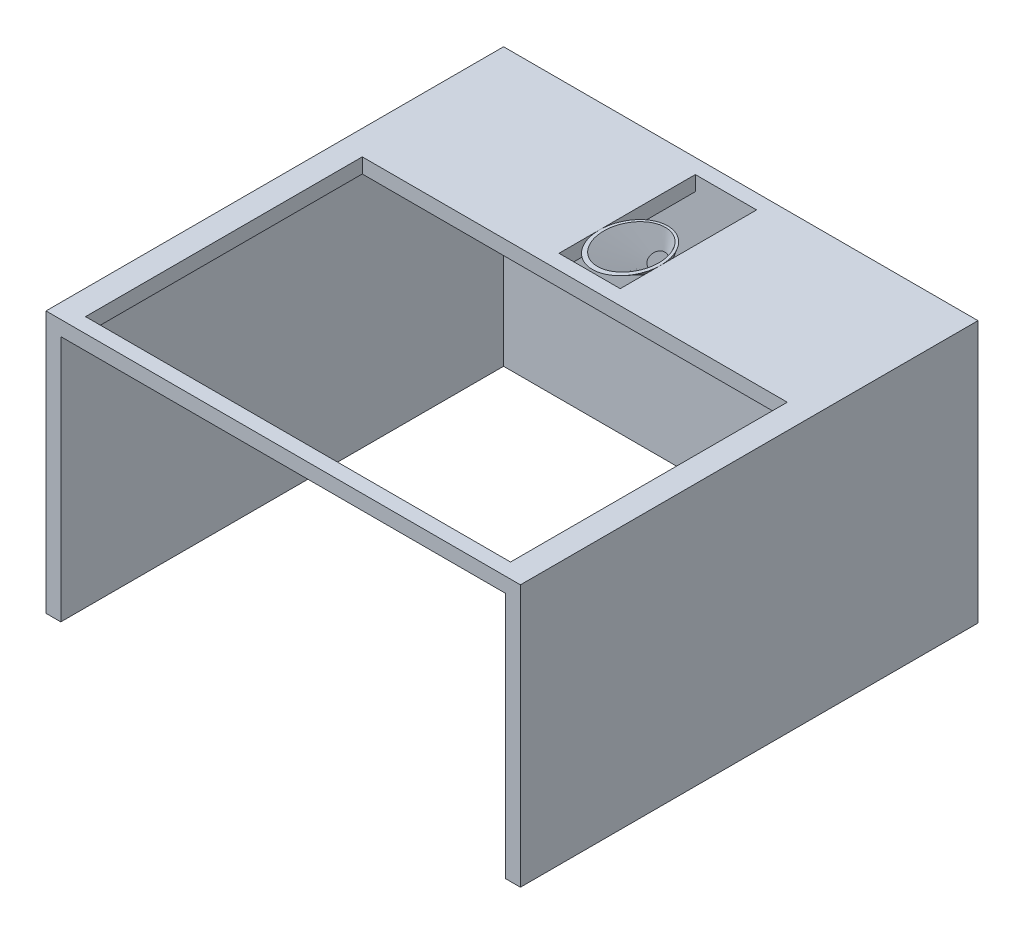
SolidWorks part; units mm, degrees
ref_plane "Front" through (0, 0, 0) normal (0, 0, 1) x (1, 0, 0)
ref_plane "Top" through (0, 0, 0) normal (0, 1, 0) x (1, 0, 0)
ref_plane "Right" through (0, 0, 0) normal (1, 0, 0) x (0, 0, -1)
sketch "Sketch1" plane through (0, 0, 0) normal (0, 1, 0) x (1, 0, 0)
  line L1 (-43, -28) -> (43, -28)
  line L2 (-43, -28) -> (-43, 28)
  line L3 (-43, 28) -> (43, 28)
  line L4 (43, -28) -> (43, 28)
  line L5 (-43, -28) -> (43, 28) construction
  line L6 (-43, 28) -> (43, -28) construction
  line L7 (-48, -31) -> (48, -31)
  line L8 (-48, -31) -> (-48, 31)
  line L9 (-48, 31) -> (48, 31)
  line L10 (48, -31) -> (48, 31)
  line L11 (-48, -31) -> (48, 31) construction
  line L12 (-48, 31) -> (48, -31) construction
  point P0 (0, 0)
  point P6 (0, 0)
  dimension "D1" = 86
  dimension "D2" = 56
  dimension "D3" = 3
  dimension "D4" = 5
extrude "Boss-Extrude1" add sketch "Sketch1" along normal blind 3
sketch "Sketch4" plane through (0, 0, 0) normal (1, 0, 0) x (0, 0, -1)
  line L0 (45.6947, -3.6988) -> (-61.4431, 55.6887) construction
  line L1 (45.6947, -3.6988) -> (-61.4431, 55.6887) construction
  line L2 (32.8171, -9.0552) -> (52.2183, 2.1461) construction
  line L3 (32.8171, -9.0552) -> (52.2183, 2.1461) construction
  line L4 (45.6947, -3.6988) -> (47.8326, 118.7791) construction
  line L5 (45.6947, -3.6988) -> (47.8326, 118.7791) construction
sketch "Sketch5" plane through (0, 0, 0) normal (1, 0, 0) x (0, 0, -1)
  line L0 (45.6947, -3.6988) -> (38.2413, 9.211) construction
  line L1 (32.8171, -9.0552) -> (52.2183, 2.1461) construction
  line L2 (45.6947, -3.6988) -> (-61.4431, 55.6887) construction
  line L3 (43.8581, -2.6807) -> (35.4738, 1.9668)
  line L4 (43.8581, -2.6807) -> (35.4738, 1.9668)
  line L7 (42.8478, -3.264) -> (29.3973, 4.1917)
  line L8 (29.3973, 4.1917) -> (35.4738, 1.9668)
  line L9 (42.8478, -3.264) -> (43.8581, -2.6807)
  line L10 (43.6157, -3.118) -> (32.4355, 3.0793)
  line L11 (43.6157, -3.118) -> (35.2314, 1.5295) construction
  dimension "D1" = 0.5
  dimension "D2" = 0.5
revolve "Revolve4" add sketch "Sketch5" angle 360 about L0
sketch "Sketch6" plane through (0, 0, -31) normal (0, 0, -1) x (-1, 0, 0)
  line L1 (48, 3) -> (-48, 3)
  line L2 (48, 3) -> (48, 16.2937)
  line L3 (48, 16.2937) -> (-48, 16.2937)
  line L4 (-48, 0) -> (48, 0)
  line L5 (48, 0) -> (48, 3)
  line L6 (48, 3) -> (-48, 3)
  line L7 (-48, 3) -> (-48, 0)
  line L8 (-48, 0) -> (48, 0)
  line L9 (48, 0) -> (48, 3)
  line L10 (48, 3) -> (-48, 3)
  line L11 (-48, 3) -> (-48, 0)
  line L12 (-48, 3) -> (-48, 16.2937)
  line M7 (48, 3) -> (-48, 3)
  dimension "D1" = 0
extrude "Cut-Extrude1" cut sketch "Sketch6" along normal through all and the other way through all contours L12 L2 L3 M7
sketch "Sketch7" plane through (0, 0, 0) normal (1, 0, 0) x (0, 0, -1)
  line L13 (32.8171, -19.124) -> (32.8171, -24.1806)
  line L14 (32.8171, -24.1806) -> (37.3171, -21.5825)
  line L15 (37.3171, -21.5825) -> (37.3171, -14.2513)
  line L16 (37.3171, -14.2513) -> (39.4389, -13.0263)
  line L17 (39.4389, -13.0263) -> (38.4389, -11.2943)
  line L18 (38.4389, -11.2943) -> (55.846, -1.2443)
  line L19 (55.846, -1.2443) -> (56.846, -2.9763)
  line L20 (56.846, -2.9763) -> (58.9678, -1.7513)
  line L21 (58.9678, -1.7513) -> (58.5928, -1.1018)
  line L22 (52.2183, 2.1461) -> (32.8171, -9.0552)
  line L23 (32.8171, -9.0552) -> (32.8171, -16.2372)
  line L24 (32.8171, -16.2372) -> (27.8171, -19.124)
  line L25 (27.8171, -19.124) -> (32.8171, -19.124)
  line L26 (32.8171, -19.124) -> (32.8171, -24.1806)
  line L27 (32.8171, -24.1806) -> (37.3171, -21.5825)
  line L28 (37.3171, -21.5825) -> (37.3171, -14.2513)
  line L29 (37.3171, -14.2513) -> (39.4389, -13.0263)
  line L30 (39.4389, -13.0263) -> (38.4389, -11.2943)
  line L31 (38.4389, -11.2943) -> (55.846, -1.2443)
  line L32 (55.846, -1.2443) -> (56.846, -2.9763)
  line L33 (56.846, -2.9763) -> (58.9678, -1.7513)
  line L34 (58.9678, -1.7513) -> (58.5928, -1.1018)
  line L35 (52.2183, 2.1461) -> (32.8171, -9.0552)
  line L36 (32.8171, -9.0552) -> (32.8171, -16.2372)
  line L37 (32.8171, -16.2372) -> (27.8171, -19.124)
  line L38 (27.8171, -19.124) -> (32.8171, -19.124)
  line L53 (58.5928, -1.1018) -> (52.2183, 2.1461)
  line L54 (58.5928, -1.1018) -> (52.2183, 2.1461)
  dimension "D1" = 0
sketch "Sketch8" plane through (0, 0, -31) normal (0, 0, -1) x (-1, 0, 0)
  line L0 (6.1993, 3) -> (-6.1993, 3) construction
  line L1 (6.1993, 3) -> (-6.1993, 3)
  line L3 (6.1993, 3) -> (-6.1993, 3)
  line L4 (-48, 0) -> (48, 0)
  line L5 (48, 0) -> (48, 3)
  line L6 (48, 3) -> (-48, 3)
  line L7 (-48, 3) -> (-48, 0)
  line L8 (-48, 0) -> (48, 0)
  line L9 (48, 0) -> (48, 3)
  line L10 (48, 3) -> (-48, 3)
  line L11 (-48, 3) -> (-48, 0)
  line L12 (6.1993, 3) -> (6.1993, 0)
  line L13 (6.1993, 0) -> (-6.1993, 0)
  line L14 (-6.1993, 3) -> (-6.1993, 0)
  line M5 (-48, 0) -> (48, 0)
  line M6 (48, 0) -> (48, 3)
  line M7 (48, 3) -> (-48, 3)
  line M8 (-48, 3) -> (-48, 0)
  dimension "D1" = 0
extrude "Boss-Extrude2" add sketch "Sketch8" along normal up to vertex (27.5928 mm away) contours L14 M7 M8 M5 | L12 L8 M7 M6 up to point (0, -1.1018, -58.5928)
sketch "Sketch9" plane through (0, 0, -58.5928) normal (0, 0, -1) x (-1, 0, 0)
  line L4 (-6.1993, 0) -> (-6.1993, 3)
  line L5 (-6.1993, 3) -> (-48, 3)
  line L6 (-48, 3) -> (-48, 0)
  line L7 (-48, 0) -> (-6.1993, 0)
  line L8 (-6.1993, 0) -> (-6.1993, 3)
  line L9 (-6.1993, 3) -> (-48, 3)
  line L10 (-48, 3) -> (-48, 0)
  line L11 (-48, 0) -> (-6.1993, 0)
  line L12 (48, 3) -> (6.1993, 3)
  line L13 (6.1993, 3) -> (6.1993, 0)
  line L14 (6.1993, 0) -> (48, 0)
  line L15 (48, 0) -> (48, 3)
  line L16 (48, 3) -> (-6.1993, 3)
  line L17 (6.1993, 3) -> (6.1993, 0)
  line L18 (-6.1993, 0) -> (48, 0)
  line L19 (48, 0) -> (48, 3)
  line M9 (-6.1993, 0) -> (-6.1993, 3)
  line M10 (-6.1993, 3) -> (-48, 3)
  line M11 (-48, 3) -> (-48, 0)
  line M12 (-48, 0) -> (-6.1993, 0)
  dimension "D1" = 0
  dimension "D2" = 0
extrude "Boss-Extrude3" add sketch "Sketch9" along normal blind 3 contours L18 L19 L16 L17 | L18 L17 L16 M9 | M12 M9 M10 M11
sketch "Sketch10" plane through (0, 0, 0) normal (0, -1, 0) x (1, 0, 0)
  line L0 (6.1993, -58.5928) -> (-6.1993, -58.5928) construction
  line L1 (48, -58.5928) -> (-48, -58.5928)
  line L3 (48, -61.5928) -> (45, -61.5928)
  line L4 (48, -61.5928) -> (48, 31)
  line L5 (48, 31) -> (-48, 31)
  line L6 (-48, 31) -> (-48, -61.5928)
  line L7 (-48, -61.5928) -> (48, -61.5928)
  line L8 (48, -61.5928) -> (48, 31)
  line L9 (48, 31) -> (-48, 31)
  line L10 (-48, 31) -> (-48, -61.5928)
  line L11 (-48, -61.5928) -> (48, -61.5928)
  line L12 (48, -61.5928) -> (48, 31)
  line L13 (48, 31) -> (45, 31)
  line L14 (45, -61.5928) -> (45, 31)
  line L15 (-48, -61.5928) -> (-45, -61.5928)
  line L16 (-48, -61.5928) -> (-48, 31)
  line L17 (-48, 31) -> (-45, 31)
  line L18 (-45, -61.5928) -> (-45, 31)
  line M6 (6.1993, -58.5928) -> (-6.1993, -58.5928)
  line M9 (48, -61.5928) -> (48, 31)
  line M10 (48, 31) -> (-48, 31)
  line M11 (-48, 31) -> (-48, -61.5928)
  line M12 (-48, -61.5928) -> (48, -61.5928)
  dimension "D2" = 3
  dimension "D3" = 3
  dimension "D1" = 0
extrude "Boss-Extrude4" add sketch "Sketch10" along normal blind 50 contours L1 M9 M6 M11 M12 | L14 L1 M9 M10 | L14 L1 M12 M9 | L1 L18 M10 M11 | L18 L1 M12 M11 | L10
